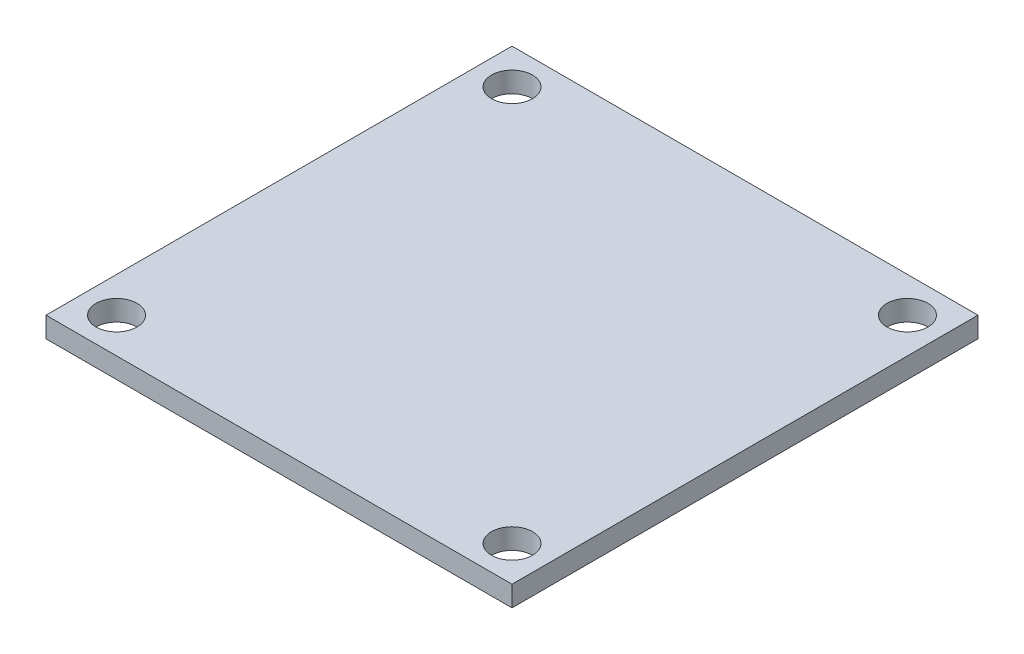
SolidWorks part; units mm, degrees
ref_plane "Front Plane" through (0, 0, 0) normal (0, 0, 1) x (1, 0, 0)
ref_plane "Top Plane" through (0, 0, 0) normal (0, 1, 0) x (1, 0, 0)
ref_plane "Right Plane" through (0, 0, 0) normal (1, 0, 0) x (0, 0, -1)
sketch "Sketch2" plane through (0, 0, 0) normal (0, 1, 0) x (1, 0, 0)
  line L0 (-15.3035, -15.3035) -> (15.3035, 15.3035) construction
  line L1 (-18.034, -18.034) -> (18.034, -18.034)
  line L2 (-18.034, -18.034) -> (-18.034, 18.034)
  line L3 (-18.034, 18.034) -> (18.034, 18.034)
  line L4 (18.034, -18.034) -> (18.034, 18.034)
  line L5 (0, 18.034) -> (0, -18.034) construction
  line L6 (-18.034, 0) -> (18.034, 0) construction
  line L7 (-15.3035, 15.3035) -> (15.3035, -15.3035) construction
  circle A0 centre (-15.3035, 15.3035) radius 1.5875
  circle A1 centre (-15.3035, -15.3035) radius 1.5875
  circle A2 centre (15.3035, -15.3035) radius 1.5875
  circle A3 centre (15.3035, 15.3035) radius 1.5875
  point P0 (0, 0)
  dimension "D3" = 3.175
  dimension "D1" = 36.068
  dimension "D2" = 30.607
extrude "Boss-Extrude1" add sketch "Sketch2" along normal mid plane 1.5875
